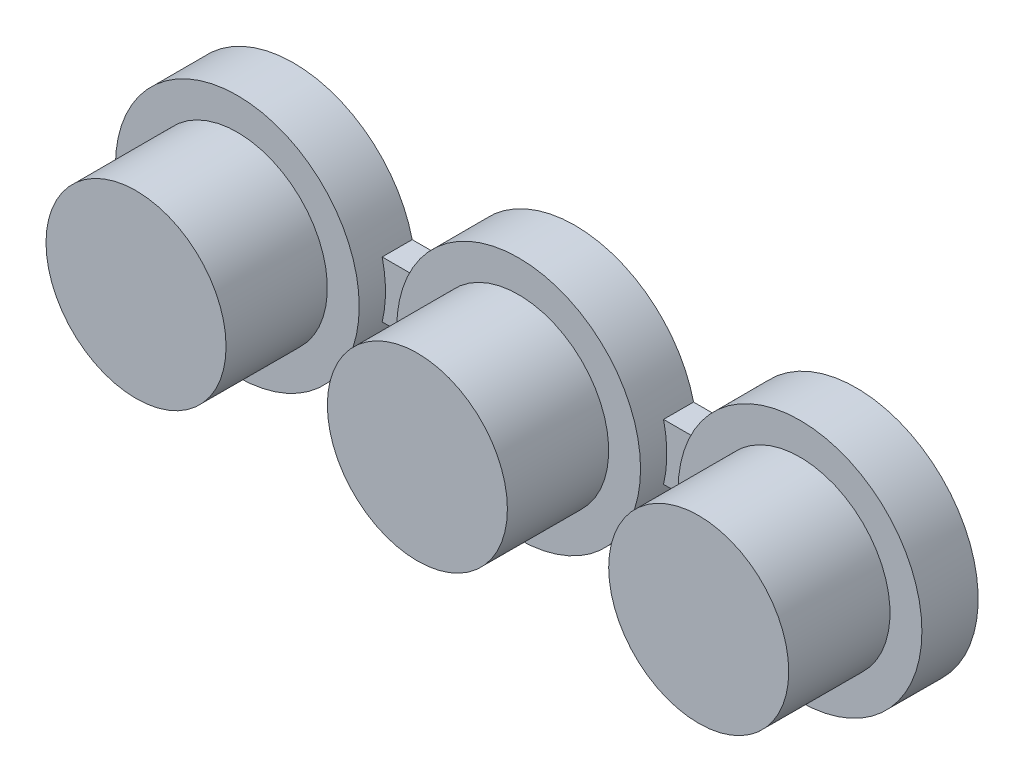
SolidWorks part; units mm, degrees
ref_plane "Front Plane" through (0, 0, 0) normal (0, 0, 1) x (1, 0, 0)
ref_plane "Top Plane" through (0, 0, 0) normal (0, 1, 0) x (1, 0, 0)
ref_plane "Right Plane" through (0, 0, 0) normal (1, 0, 0) x (0, 0, -1)
sketch "Sketch1" plane through (0, 0, 0) normal (0, 0, 1) x (1, 0, 0)
  line L0 (-7.5, 0) -> (7.5, 0) construction
  circle A0 centre (-7.5, 0) radius 2.4
  circle A1 centre (0, 0) radius 2.4
  circle A2 centre (7.5, 0) radius 2.4
  dimension "D2" = 4.8
  dimension "D1" = 15
extrude "Boss-Extrude1" add sketch "Sketch1" along normal blind 4.2
sketch "Sketch2" plane through (0, 0, 0) normal (0, 0, -1) x (-1, 0, 0)
  line L1 (7.3316, -0.75) -> (-7.3316, -0.75)
  line L2 (7.3316, -0.75) -> (7.3316, 0.75)
  line L3 (7.3316, 0.75) -> (-7.3316, 0.75)
  line L4 (-7.3316, -0.75) -> (-7.3316, 0.75)
  line L5 (7.3316, -0.75) -> (-7.3316, 0.75) construction
  line L6 (7.3316, 0.75) -> (-7.3316, -0.75) construction
  point P0 (0, 0)
  dimension "D1" = 1.5
extrude "Boss-Extrude2" add sketch "Sketch2" against normal blind 0.8
sketch "Sketch3" plane through (0, 0, 0) normal (0, 0, -1) x (-1, 0, 0)
  circle A0 centre (0, 0) radius 3.25
  circle A1 centre (7.5, 0) radius 3.25
  circle A2 centre (-7.5, 0) radius 3.25
  dimension "D1" = 6.5
extrude "Boss-Extrude3" add sketch "Sketch3" against normal blind 1.5
